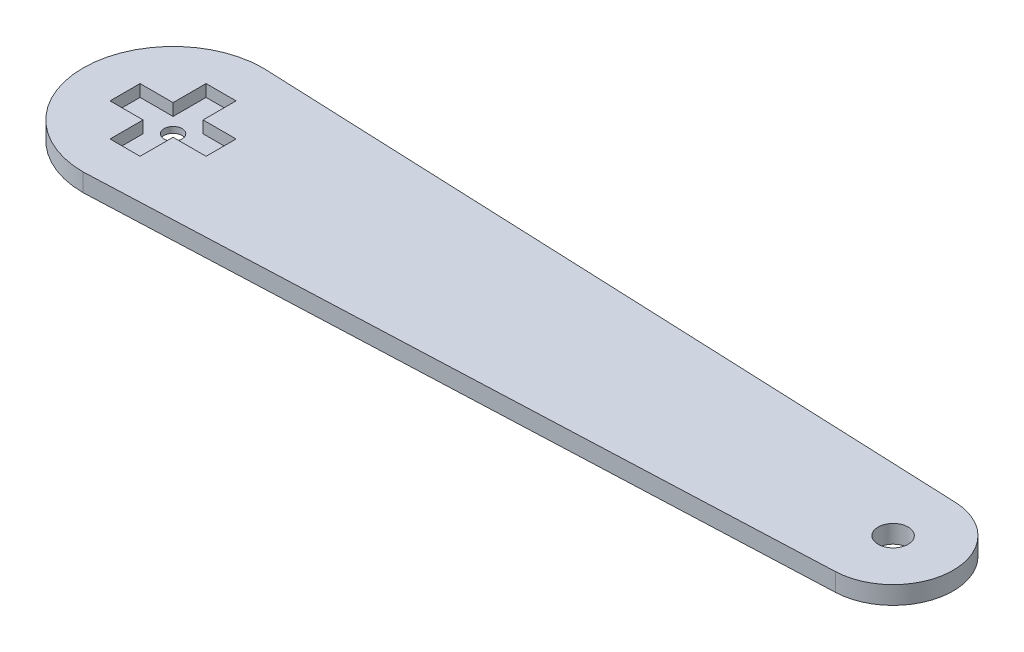
SolidWorks part; units mm, degrees
ref_plane "前视基准面" through (0, 0, 0) normal (0, 0, 1) x (1, 0, 0)
ref_plane "上视基准面" through (0, 0, 0) normal (0, 1, 0) x (1, 0, 0)
ref_plane "右视基准面" through (0, 0, 0) normal (1, 0, 0) x (0, 0, -1)
other "Configuration Table"
sketch "草图1" plane through (0, 0, 0) normal (0, 1, 0) x (1, 0, 0)
  line L0 (0, 0) -> (120, 0)
  line L1 (0, 15) -> (120.4156, 9.9914)
  line L2 (0, -15) -> (120.4156, -9.9914)
  circle A0 centre (0, 0) radius 15
  circle A1 centre (120, 0) radius 10
  circle A2 centre (0, 0) radius 5
  dimension "D1" = 30
  dimension "D3" = 20
  dimension "D4" = 10
  dimension "D2" = 120
extrude "凸台-拉伸1" add sketch "草图1" along normal blind 3
sketch "草图2" plane through (0, 3, 0) normal (0, 1, 0) x (1, 0, 0)
  circle A0 centre (120, 0) radius 2.5
  dimension "D1" = 5
extrude "切除-拉伸1" cut sketch "草图2" against normal through all
sketch "草图3" plane through (0, 3, 0) normal (0, 1, 0) x (1, 0, 0)
  circle A0 centre (0, 0) radius 5
extrude "凸台-拉伸2" add sketch "草图3" against normal blind 3
sketch "草图4" plane through (0, 3, 0) normal (0, 1, 0) x (1, 0, 0)
  circle A0 centre (0, 0) radius 1.5
  dimension "D1" = 3
extrude "切除-拉伸2" cut sketch "草图4" against normal blind 3
sketch "草图5" plane through (0, 3, 0) normal (0, 1, 0) x (1, 0, 0)
  line L1 (-8, -2.5) -> (8, -2.5)
  line L2 (-8, -2.5) -> (-8, 2.5)
  line L3 (-8, 2.5) -> (8, 2.5)
  line L4 (8, -2.5) -> (8, 2.5)
  line L5 (-8, -2.5) -> (8, 2.5) construction
  line L6 (-8, 2.5) -> (8, -2.5) construction
  line L7 (-2.5, -8) -> (2.5, -8)
  line L8 (-2.5, -8) -> (-2.5, 8)
  line L9 (-2.5, 8) -> (2.5, 8)
  line L10 (2.5, -8) -> (2.5, 8)
  line L11 (-2.5, -8) -> (2.5, 8) construction
  line L12 (-2.5, 8) -> (2.5, -8) construction
  point P0 (0, 0)
  point P6 (0, 0)
  circle M5 centre (0, 0) radius 1.5
  dimension "D1" = 16
  dimension "D2" = 5
  dimension "D3" = 16
  dimension "D4" = 5
extrude "切除-拉伸3" cut sketch "草图5" against normal blind 2 contours L3 L10 L9 L8 | L1 L8 L3 L2 | L7 L10 L1 L8 | L10 L1 L4 L3 | L1 L10 L3 L8 M5
